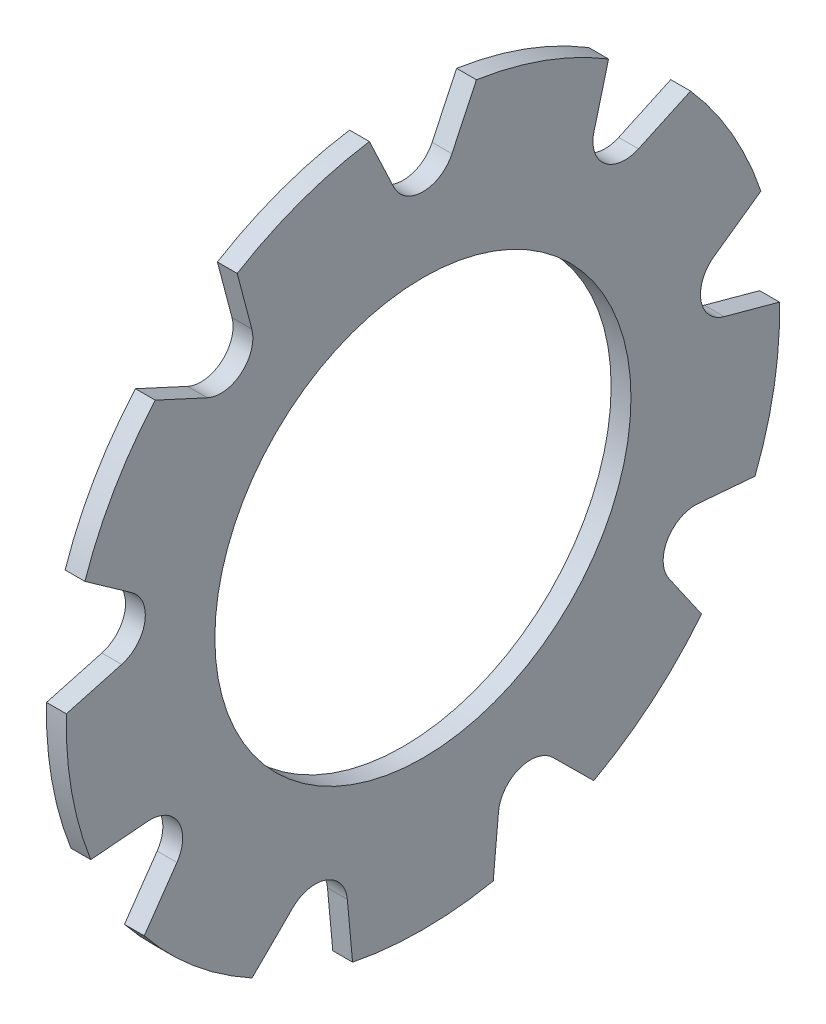
SolidWorks part; units mm, degrees
extrude "Base-Extrude" add sketch "Sketch1" against normal blind 0.5
sketch "Sketch1" plane through (0, 0, 0) normal (1, 0, 0) x (0, 0, -1)
  circle A0 centre (0, 0) radius 5.25
  circle A1 centre (0, 0) radius 9
  dimension "InsideDia" = 10.5
  dimension "OutsideDia" = 18
ref_plane "Plane1" through (0, 0, 0) normal (0, 0, 1) x (1, 0, 0)
ref_plane "Plane2" through (0, 0, 0) normal (0, 1, 0) x (1, 0, 0)
ref_plane "Plane3" through (0, 0, 0) normal (1, 0, 0) x (0, 0, -1)
sketch "Sketch3" plane through (0, 0, 0) normal (1, 0, 0) x (0, 0, -1)
  line L0 (0.7326, 7.5894) -> (1.35, 8.8982)
  line L1 (-0.7326, 7.5894) -> (-1.35, 8.8982)
  line L2 (-1.35, 8.8982) -> (-1.35, 9.7082)
  line L3 (-1.35, 9.7082) -> (1.35, 9.7082)
  line L4 (1.35, 9.7082) -> (1.35, 8.8982)
  arc A0 (-0.7326, 7.5894) -> (0.7326, 7.5894) centre (0, 7.935) ccw
  circle A1 centre (0, 0) radius 9 construction
  circle A2 centre (0, 0) radius 7.125 construction
  dimension "D1" = 1.62
  dimension "D4" = 14.25
  dimension "D2" = 2.7
  dimension "D3" = 0.81
  dimension "D5" = 1.35
extrude "TypeASlot" cut sketch "Sketch3" against normal through all
pattern_circular "TypeAPattern" count 9 over 360 about axis through (0, 0, 0) along (1, 0, 0) of "TypeASlot"
sketch "Sketch2" plane through (0, 0, 0) normal (1, 0, 0) x (0, 0, -1)
  line L0 (0.81, 0) -> (0.81, 6.315)
  line L1 (-0.81, 6.315) -> (-0.81, 0)
  line L2 (-0.81, 0) -> (0.81, 0)
  arc A0 (0.81, 6.315) -> (-0.81, 6.315) centre (0, 6.315) ccw
  circle A3 centre (0, 0) radius 7.125 construction
  dimension "D1" = 14.25
  dimension "SlotWidth" = 1.62
extrude "TypeJSlot" [suppressed] cut sketch "Sketch2" against normal through all
pattern_circular "TypeJPattern" [suppressed] count 9 over 360
equation "\"SlotWidth@Sketch2\" = \"OutsideDia@Sketch1\" * .09"
equation "\"D1@Sketch2\" = \"InsideDia@Sketch1\" +  ( \"OutsideDia@Sketch1\" - \"InsideDia@Sketch1\" )  / 2"
equation "\"D1@Sketch3\" = \"OutsideDia@Sketch1\" * .09"
equation "\"D2@Sketch3\" = \"OutsideDia@Sketch1\" * .15"
equation "\"D3@Sketch3\" = \"D1@Sketch3\" / 2"
equation "\"D4@Sketch3\" = \"InsideDia@Sketch1\" +  ( \"OutsideDia@Sketch1\" - \"InsideDia@Sketch1\" )  / 2"
equation "\"D5@Sketch3\" = \"D2@Sketch3\" / 2"
